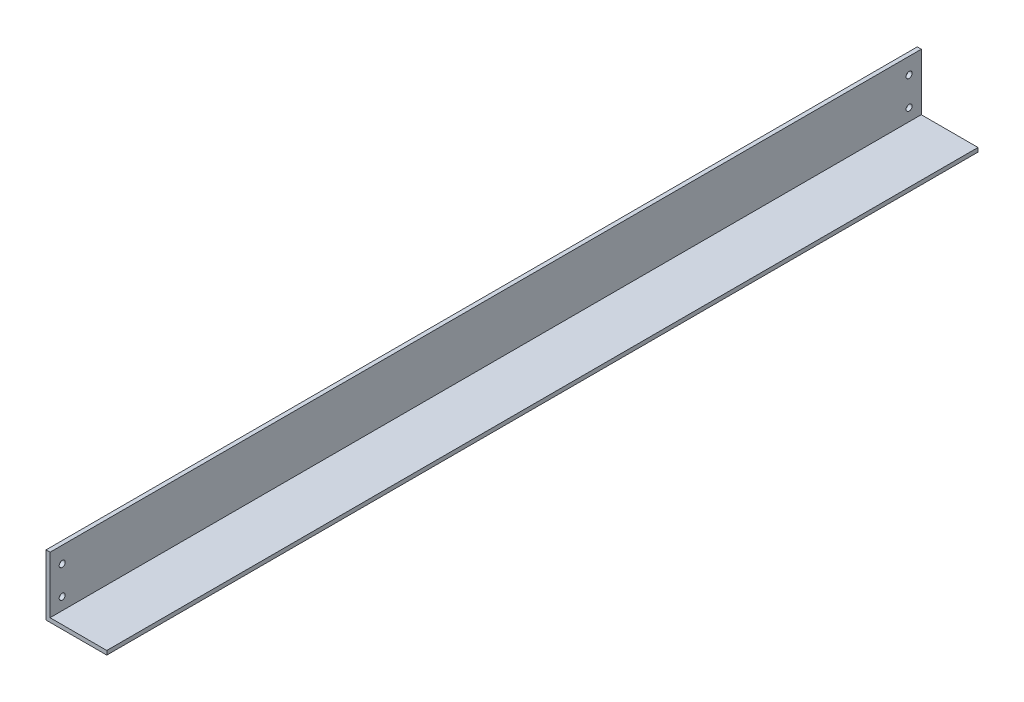
SolidWorks part; units mm, degrees
material "1060 Alloy"
ref_plane "Front Plane" through (0, 0, 0) normal (0, 0, 1) x (1, 0, 0)
ref_plane "Top Plane" through (0, 0, 0) normal (0, 1, 0) x (1, 0, 0)
ref_plane "Right Plane" through (0, 0, 0) normal (1, 0, 0) x (0, 0, -1)
sketch "Sketch1" plane through (0, 0, 0) normal (0, 0, 1) x (1, 0, 0)
  line L0 (0, 5.6023) -> (0, 35.6023)
  line L1 (0, 35.6023) -> (2, 35.6023)
  line L2 (2, 35.6023) -> (2, 7.6023)
  line L3 (2, 7.6023) -> (30, 7.6023)
  line L4 (30, 7.6023) -> (30, 5.6023)
  line L5 (30, 5.6023) -> (0, 5.6023)
extrude "Boss-Extrude1" add sketch "Sketch1" along normal blind 410 and the other way up to vertex (20 mm away)
hole_wizard "Ø3.0 (3) Diameter Hole2" positions "Sketch4" profile "Sketch5" hole size "Ø3.0" standard "ISO" end condition through all
sketch "Sketch4" plane through (0, 369.01, 221.32) normal (-1, 0, 0) x (0, 0, -1)
  point P0 (235.32, 341.4076)
  point P2 (235.32, 355.4076)
  point P7 (0, 0)
  point P8 (0, 0)
  point P9 (235.32, 353.6335)
  point P10 (0, 0)
sketch "Sketch5" plane through (0, 27.6023, -14) normal (0, 1, 0) x (0, 0, 1)
  line L0 (0, 0) -> (0, 30)
  line L1 (0, 30) -> (1.5, 30)
  line L2 (1.5, 30) -> (1.5, 0)
  line L3 (1.5, 0) -> (0, 0)
  line L4 (0, -6.35) -> (0, 107.95) construction
  dimension "Thru Hole Dia." = 3
  dimension "Thru Hole Depth" = 30
hole_wizard "Ø3.0 (3) Diameter Hole4" positions "Sketch8" profile "Sketch9" hole size "Ø3.0" standard "ISO"
sketch "Sketch8" plane through (2, 369.01, 221.32) normal (1, 0, 0) x (0, 0, 1)
  point P0 (182.68, 355.4076)
  point P1 (182.68, 341.4076)
sketch "Sketch9" plane through (2, 13.6023, 404) normal (0, 1, 0) x (0, 0, -1)
  line L0 (0, 0) -> (0, 1.999)
  line L1 (0, 1.999) -> (1.5, 1.999)
  line L2 (1.5, 1.999) -> (1.5, 0)
  line L3 (1.5, 0) -> (0, 0)
  line L4 (0, -6.35) -> (0, 107.95) construction
  dimension "Thru Hole Dia." = 3
  dimension "Thru Hole Depth" = 1.999
